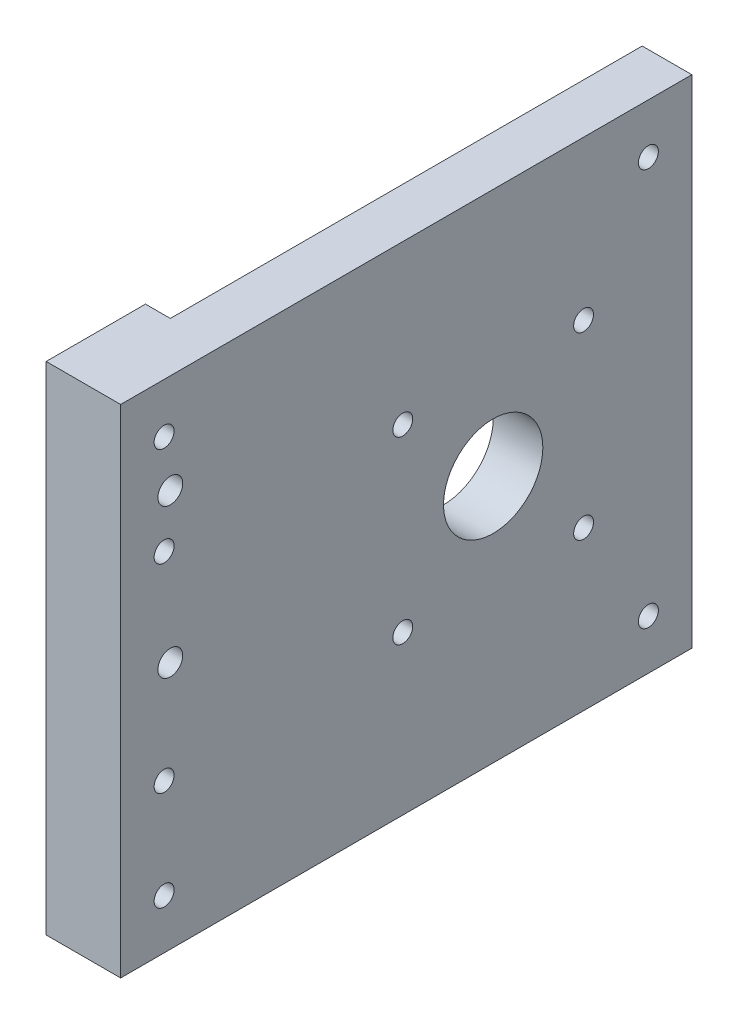
SolidWorks part; units mm, degrees
ref_plane "Front Plane" through (0, 0, 0) normal (0, 0, 1) x (1, 0, 0)
ref_plane "Top Plane" through (0, 0, 0) normal (0, 1, 0) x (1, 0, 0)
ref_plane "Right Plane" through (0, 0, 0) normal (1, 0, 0) x (0, 0, -1)
sketch "Sketch1" plane through (0, 0, 0) normal (0, 0, 1) x (1, 0, 0)
  line L1 (0, 0) -> (12.7, 0)
  line L2 (0, 0) -> (0, 127)
  line L3 (0, 127) -> (12.7, 127)
  line L4 (12.7, 0) -> (12.7, 127)
  dimension "D1" = 127
  dimension "D2" = 12.7
extrude "Boss-Extrude1" add sketch "Sketch1" along normal blind 146.05
sketch "Sketch3" plane through (12.7, 0, 0) normal (1, 0, 0) x (0, 0, -1)
  line L0 (-146.05, 63.5) -> (-50.8, 63.5) construction
  line L1 (-146.05, 0) -> (-146.05, 127) construction
  line L2 (-146.05, 127) -> (-133.35, 127)
  line L3 (-73.914, 40.513) -> (-27.686, 40.513) construction
  line L4 (-73.914, 40.513) -> (-73.914, 86.487) construction
  line L5 (-73.914, 86.487) -> (-27.686, 86.487) construction
  line L6 (-27.686, 40.513) -> (-27.686, 86.487) construction
  line L7 (-73.914, 40.513) -> (-27.686, 86.487) construction
  line L8 (-73.914, 86.487) -> (-27.686, 40.513) construction
  line L9 (-146.05, 127) -> (0, 127) construction
  line L12 (-133.35, 101.6) -> (-133.35, 63.5)
  circle A0 centre (-50.8, 63.5) radius 12.7
  circle A1 centre (-73.914, 86.487) radius 2.54
  circle A2 centre (-27.686, 86.487) radius 2.54
  circle A3 centre (-27.686, 40.513) radius 2.54
  circle A4 centre (-73.914, 40.513) radius 2.54
  circle A5 centre (-133.35, 63.5) radius 3.175
  circle A6 centre (-133.35, 101.6) radius 3.175
  dimension "D2" = 25.4
  dimension "D5" = 5.08
  dimension "D6" = 5.08
  dimension "D7" = 5.08
  dimension "D8" = 5.08
  dimension "D11" = 6.35
  dimension "D12" = 6.35
  dimension "D1" = 95.25
  dimension "D3" = 45.974
  dimension "D4" = 46.228
  dimension "D9" = 12.7
  dimension "D10" = 38.1
extrude "Cut-Extrude1" cut sketch "Sketch3" against normal up to surface (12.7 mm away)
sketch "Sketch4" plane through (0, 0, 0) normal (-1, 0, 0) x (0, 0, 1)
  line L0 (146.05, 0) -> (0, 0) construction
  line L1 (146.05, 127) -> (120.65, 127)
  line L2 (146.05, 127) -> (146.05, 0)
  line L3 (146.05, 0) -> (120.65, 0)
  line L4 (120.65, 127) -> (120.65, 0)
  dimension "D1" = 25.4
extrude "Boss-Extrude2" add sketch "Sketch4" along normal blind 6.35 contours L2 L1 L4 L3
sketch "Sketch5" plane through (12.7, 0, 0) normal (1, 0, 0) x (0, 0, -1)
  line L0 (-73.914, 86.487) -> (-73.914, 127)
  line L1 (-146.05, 127) -> (0, 127) construction
  line L2 (-27.686, 86.487) -> (-27.686, 40.513)
  line L3 (-27.686, 86.487) -> (0, 86.487)
  line L4 (0, 0) -> (0, 127) construction
  circle A0 centre (-50.8, 63.5) radius 25.019
  circle A1 centre (-73.914, 86.487) radius 2.54
  dimension "D1" = 50.038
  dimension "D2" = 5.08
  dimension "D3" = 27.686
sketch "Sketch8" plane through (-6.35, 0, 0) normal (-1, 0, 0) x (0, 0, 1)
  line L1 (120.65, 127) -> (146.05, 127)
  line L2 (120.65, 127) -> (120.65, 0)
  line L3 (120.65, 0) -> (146.05, 0)
  line L4 (146.05, 127) -> (146.05, 0)
sketch "Sketch9" plane through (0, 0, 0) normal (1, 0, 0) x (0, 0, -1)
  circle A0 centre (-133.35, 101.6) radius 3.175
  circle A1 centre (-133.35, 63.5) radius 3.175
extrude "Cut-Extrude2" cut sketch "Sketch9" against normal through all
hole_wizard "1/4-20 Tapped Hole1" positions "Sketch10" profile "Sketch11" tap size "1/4-20" standard "ANSI Inch" end condition through all
sketch "Sketch10" plane through (0, 0, 0) normal (-1, 0, 0) x (0, 0, 1)
  line L0 (0, 127) -> (0, 0) construction
  line L1 (120.65, 127) -> (0, 127) construction
  line L2 (120.65, 0) -> (0, 0) construction
  point P0 (11.1125, 114.3)
  point P2 (11.1125, 12.7)
  dimension "D1" = 11.1125
  dimension "D2" = 12.7
  dimension "D3" = 12.7
sketch "Sketch11" plane through (0, 114.3, 11.1125) normal (0, 1, 0) x (0, 0, 1)
  line L0 (0, 0) -> (0, 12.7)
  line L1 (0, 12.7) -> (2.5527, 12.7)
  line L2 (2.5527, 12.7) -> (2.5527, 0)
  line L5 (2.5527, 0) -> (0, 0)
  line L11 (0, -6.35) -> (0, 107.95) construction
  dimension "Thru Tap Drill Dia." = 5.1054
  dimension "Thru Tap Drill Depth" = 12.7
cosmetic thread "Hole Thread1" parameters "D2"=6.35
cosmetic thread "Hole Thread2" parameters "D2"=6.35
hole_wizard "1/4-20 Tapped Hole2" positions "Sketch12" profile "Sketch13" tap size "1/4-20" standard "ANSI Inch" end condition through all
sketch "Sketch12" plane through (-6.35, 0, 0) normal (-1, 0, 0) x (0, 0, 1)
  line L0 (146.05, 127) -> (120.65, 127) construction
  line L1 (146.05, 0) -> (120.65, 0) construction
  line L2 (146.05, 127) -> (146.05, 0) construction
  point P0 (134.9375, 114.3)
  point P2 (134.9375, 88.9)
  point P4 (134.9375, 38.1)
  point P6 (134.9375, 12.7)
  point P9 (0, 0)
  dimension "D1" = 12.7
  dimension "D2" = 25.4
  dimension "D3" = 12.7
  dimension "D4" = 25.4
  dimension "D5" = 11.1125
sketch "Sketch13" plane through (-6.35, 114.3, 134.9375) normal (0, 1, 0) x (0, 0, 1)
  line L0 (0, 0) -> (0, 19.05)
  line L1 (0, 19.05) -> (2.5527, 19.05)
  line L2 (2.5527, 19.05) -> (2.5527, 0)
  line L5 (2.5527, 0) -> (0, 0)
  line L11 (0, -6.35) -> (0, 107.95) construction
  dimension "Thru Tap Drill Dia." = 5.1054
  dimension "Thru Tap Drill Depth" = 19.05
cosmetic thread "Hole Thread3" parameters "D2"=6.35
cosmetic thread "Hole Thread4" parameters "D2"=6.35
cosmetic thread "Hole Thread5" parameters "D2"=6.35
cosmetic thread "Hole Thread6" parameters "D2"=6.35
